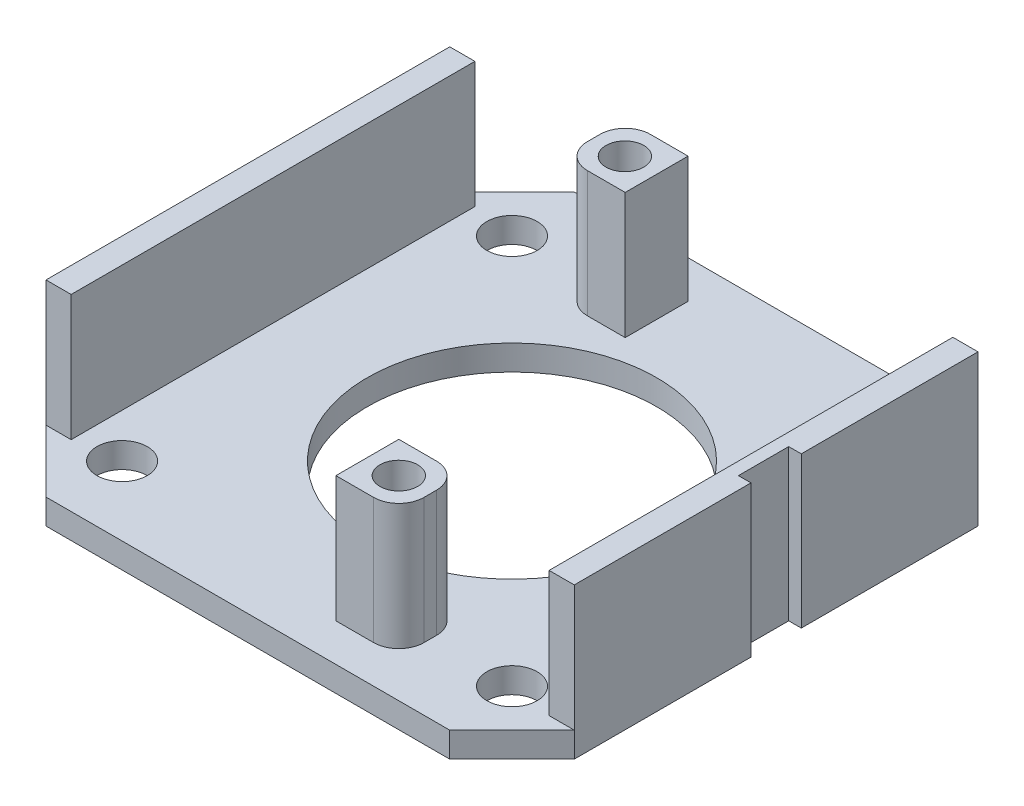
SolidWorks part; units mm, degrees
ref_plane "Front Plane" through (0, 0, 0) normal (0, 0, 1) x (1, 0, 0)
ref_plane "Top Plane" through (0, 0, 0) normal (0, 1, 0) x (1, 0, 0)
ref_plane "Right Plane" through (0, 0, 0) normal (1, 0, 0) x (0, 0, -1)
sketch "Sketch1" plane through (0, 0, 0) normal (0, 1, 0) x (1, 0, 0)
  line L1 (-21, -21) -> (21, -21)
  line L2 (-21, -21) -> (-21, 21)
  line L3 (-21, 21) -> (21, 21)
  line L4 (21, -21) -> (21, 21)
  line L5 (-21, -21) -> (21, 21) construction
  line L6 (-21, 21) -> (21, -21) construction
  point P0 (0, 0)
  dimension "D1" = 42
extrude "Boss-Extrude1" add sketch "Sketch1" along normal blind 2
sketch "Sketch2" plane through (0, 2, 0) normal (0, 1, 0) x (1, 0, 0)
  circle A0 centre (0, 0) radius 11.5
  dimension "D1" = 23
extrude "Cut-Extrude1" cut sketch "Sketch2" against normal through all
sketch "Sketch3" plane through (0, 2, 0) normal (0, 1, 0) x (1, 0, 0)
  line L0 (-15.5, 15.5) -> (0, 0) construction
  line L1 (-15.5, -15.5) -> (15.5, -15.5) construction
  line L2 (-15.5, -15.5) -> (-15.5, 15.5) construction
  line L3 (-15.5, 15.5) -> (15.5, 15.5) construction
  line L4 (15.5, -15.5) -> (15.5, 15.5) construction
  line L5 (-15.5, -15.5) -> (0, 0) construction
  line L6 (0, 0) -> (15.5, -15.5) construction
  line L7 (0, 0) -> (15.5, 15.5) construction
  circle A0 centre (-15.5, 15.5) radius 2
  circle A1 centre (15.5, 15.5) radius 2
  circle A2 centre (15.5, -15.5) radius 2
  circle A3 centre (-15.5, -15.5) radius 2
  point P0 (0, 0)
  dimension "D3" = 4
  dimension "D1" = 31
  dimension "D2" = 31
extrude "Cut-Extrude2" cut sketch "Sketch3" against normal through all
sketch "Sketch4" plane through (0, 2, 0) normal (0, 1, 0) x (1, 0, 0)
  line L0 (-21, 16.0503) -> (-16.0503, 21)
  line L1 (-21, 21) -> (-21, -21) construction
  line L2 (21, 21) -> (-21, 21) construction
  line L3 (-16.0503, 21) -> (-21, 21)
  line L4 (-21, 21) -> (-21, 16.0503)
  line L5 (-21, -21) -> (-16.0503, -21)
  line L6 (-21, -21) -> (21, -21) construction
  line L7 (-16.0503, -21) -> (-21, -16.0503)
  line L8 (-21, -16.0503) -> (-21, -21)
  line L9 (21, -21) -> (16.0503, -21)
  line L10 (16.0503, -21) -> (21, -16.0503)
  line L11 (21, -21) -> (21, 21) construction
  line L12 (21, -16.0503) -> (21, -21)
  line L13 (16.0503, 21) -> (21, 16.0503)
  line L14 (21, 16.0503) -> (21, 21)
  line L15 (21, 21) -> (16.0503, 21)
  line L16 (0, 0) -> (8.5208, 0) construction
  line L17 (0, 0) -> (-4.1043, 4.1043) construction
  dimension "D1" = 7
  dimension "D5" = 135
extrude "Cut-Extrude3" cut sketch "Sketch4" against normal through all
sketch "Sketch5" plane through (0, 2, 0) normal (0, 1, 0) x (1, 0, 0)
  line L4 (-21, 16.0503) -> (-21, -16.0503)
  line L9 (-21, 16.0503) -> (-19, 16.0503)
  line L10 (-21, -16.0503) -> (-19, -16.0503)
  line L11 (-19, 16.0503) -> (-19, -16.0503)
  line L12 (0, 5.0585) -> (0, -4.3373) construction
  line L13 (19, 16.0503) -> (19, -16.0503)
  line L14 (21, -16.0503) -> (19, -16.0503)
  line L15 (21, 16.0503) -> (19, 16.0503)
  line L16 (21, 16.0503) -> (21, -16.0503)
  dimension "D1" = 2
  dimension "D2" = 32.1005
extrude "Boss-Extrude2" add sketch "Sketch5" along normal blind 10
sketch "Sketch6" plane through (0, 2, 0) normal (0, 1, 0) x (1, 0, 0)
  line L0 (19, 16.0503) -> (19, -16.0503) construction
  line L1 (-19, -16.0503) -> (-19, 16.0503) construction
  line L2 (0, 15.5) -> (0, -15.5) construction
  line L3 (4.7653, 0) -> (-4.322, 0) construction
  line L4 (4, -13) -> (9, -13)
  line L5 (4, -13) -> (4, -18)
  line L6 (4, -18) -> (9, -18)
  line L7 (9, -13) -> (9, -18)
  line L8 (4, -13) -> (9, -18) construction
  line L9 (4, -18) -> (9, -13) construction
  line L10 (-9, 18) -> (-4, 18)
  line L11 (-9, 18) -> (-9, 13)
  line L12 (-9, 13) -> (-4, 13)
  line L13 (-4, 18) -> (-4, 13)
  line L14 (-9, 18) -> (-4, 13) construction
  line L15 (-9, 13) -> (-4, 18) construction
  line L16 (16.0503, 21) -> (-16.0503, 21) construction
  line L17 (-16.0503, -21) -> (16.0503, -21) construction
  point P1 (6.5, -15.5)
  point P16 (-6.5, 15.5)
  point P21 (-9, 15.5)
  dimension "D1" = 5
  dimension "D2" = 10
  dimension "D3" = 10
  dimension "D4" = 3
  dimension "D5" = 3
extrude "Boss-Extrude3" add sketch "Sketch6" along normal up to surface (10 mm away) up to face at (20, 12, 0)
sketch "Sketch7" plane through (0, 2, 0) normal (0, 1, 0) x (1, 0, 0)
  line L0 (-21, -75) -> (-21, 75)
  line L1 (-21, -75) -> (21, -75)
  line L2 (-21, 75) -> (21, 75)
  line L3 (21, -75) -> (21, 75)
  line L4 (-21, -75) -> (21, 75) construction
  line L5 (-21, 75) -> (21, -75) construction
  line L6 (-21, 16.0503) -> (-16.0503, 21)
  line L7 (-16.0503, 21) -> (16.0503, 21)
  line L8 (16.0503, 21) -> (21, 16.0503)
  line L9 (-21, -16.0503) -> (-16.0503, -21)
  line L10 (-16.0503, -21) -> (16.0503, -21)
  line L11 (16.0503, -21) -> (21, -16.0503)
  circle A0 centre (0, 0) radius 11.5
  circle A1 centre (-15.5, 15.5) radius 2
  circle A2 centre (15.5, 15.5) radius 2
  circle A3 centre (-15.5, -15.5) radius 2
  circle A4 centre (15.5, -15.5) radius 2
  point P1 (0, 0)
  line M13 (21, 16.0503) -> (16.0503, 21)
  line M14 (16.0503, 21) -> (-16.0503, 21)
  line M15 (-16.0503, 21) -> (-21, 16.0503)
  line M19 (-21, -16.0503) -> (-16.0503, -21)
  line M20 (-16.0503, -21) -> (16.0503, -21)
  line M21 (16.0503, -21) -> (21, -16.0503)
  dimension "D1" = 42
  dimension "D2" = 150
extrude "Boss-Extrude5" [suppressed] add sketch "Sketch7" against normal blind 2 contours L3 L2 L0 M13 M15 M14 | L1 L3 L0 M21 M20 M19
sketch "Sketch8" [suppressed] plane through (0, 2, 0) normal (0, 1, 0) x (1, 0, 0)
  line L0 (-21, 75) -> (21, 75)
  line L1 (21, 75) -> (21, -75)
  line L2 (21, -75) -> (-21, -75)
  line L3 (-21, -75) -> (-21, 75)
  circle A0 centre (0, 0) radius 77.8845
  line M2 (-21, -16.0503) -> (-21, -75)
  line M3 (-21, -75) -> (21, -75)
  line M4 (21, -75) -> (21, -16.0503)
  line M8 (21, 16.0503) -> (21, 75)
  line M9 (21, 75) -> (-21, 75)
  line M10 (-21, 75) -> (-21, 16.0503)
extrude "Boss-Extrude6" [suppressed] add sketch "Sketch8" against normal blind 2 contours A0 L3 M10 M2 | A0 M9 | A0 L1 M4 M8 | A0 M3
sketch "Sketch9" plane through (21, 0, 0) normal (1, 0, 0) x (0, 0, -1)
  line L0 (0, 12) -> (0, 0) construction
  line L1 (-16.0503, 12) -> (16.0503, 12) construction
  line L2 (-2, 0) -> (-2, 12)
  line L3 (-2, 0) -> (2, 0)
  line L4 (-2, 12) -> (2, 12)
  line L5 (2, 0) -> (2, 12)
  line L6 (-2, 0) -> (2, 12) construction
  line L7 (-2, 12) -> (2, 0) construction
  point P6 (0, 6)
  dimension "D1" = 4
extrude "Cut-Extrude4" cut sketch "Sketch9" against normal blind 1
sketch "Sketch11" plane through (0, 12, 0) normal (0, 1, 0) x (1, 0, 0)
  line L0 (-9, 13) -> (-4, 13) construction
  line L1 (-9, 13) -> (-9, 17.9493) construction
  line L2 (-4, 13) -> (-4, 17.9493) construction
  line L3 (-9, 17.9493) -> (-4, 17.9493) construction
  line L4 (4, -18) -> (9, -18) construction
  line L5 (4, -18) -> (4, -13) construction
  line L6 (9, -18) -> (9, -13) construction
  line L7 (4, -13) -> (9, -13) construction
  line L8 (9, -13) -> (4, -13) construction
  line L9 (-9, 17.9493) -> (-6.5, 15.4747) construction
  line L10 (-6.5, 15.4747) -> (-9, 13) construction
  line L11 (4, -13) -> (6.5, -15.5) construction
  line L12 (6.5, -15.5) -> (4, -18) construction
  line L13 (-4, 17.9493) -> (-6.5, 15.4747) construction
  line L14 (-6.5, 15.4747) -> (-4, 13) construction
  line L15 (9, -13) -> (6.5, -15.5) construction
  line L16 (6.5, -15.5) -> (9, -18) construction
  circle A0 centre (-6.5, 15.4747) radius 1.5
  circle A1 centre (6.5, -15.5) radius 1.5
  dimension "D1" = 3
extrude "Cut-Extrude5" cut sketch "Sketch11" against normal blind 4
fillet "Fillet1" radius 2 4 edges at (-9, 7, -18) (-9, 7, -13) (9, 7, 18) (9, 7, 13)
